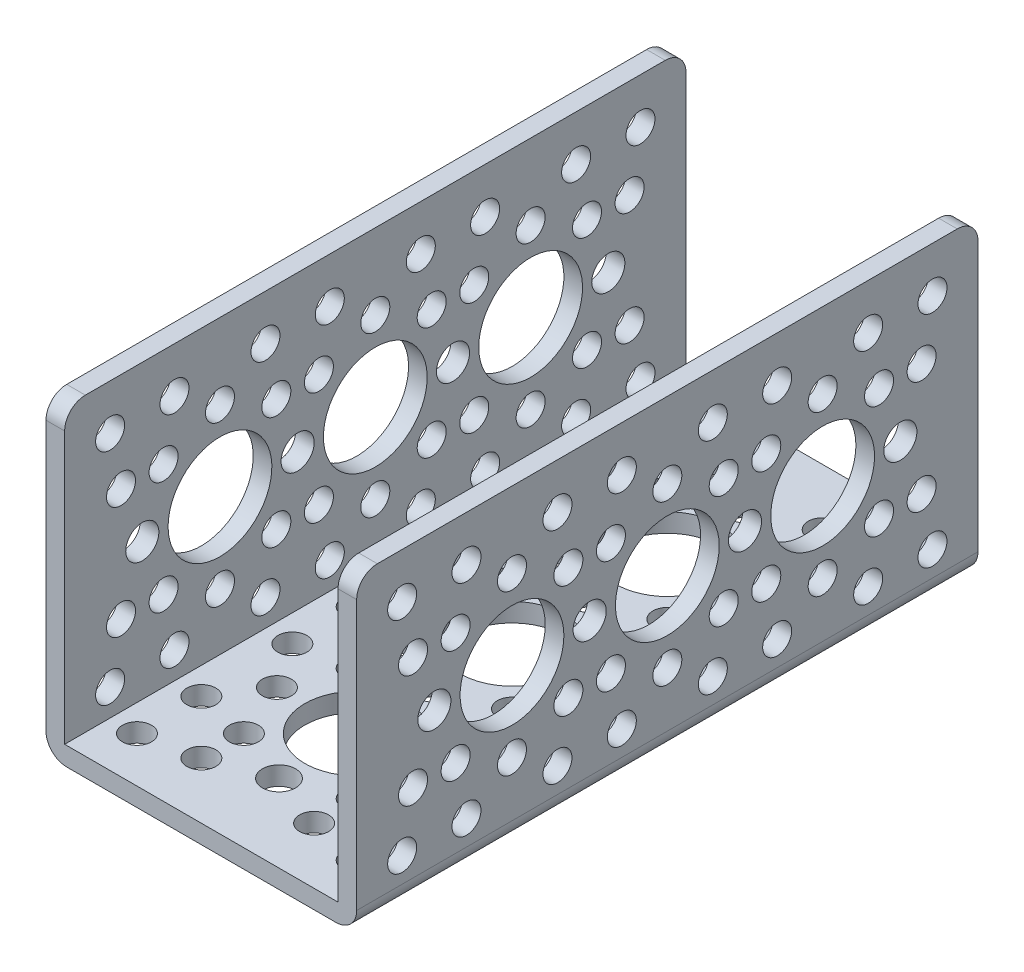
SolidWorks part; units mm, degrees
ref_plane "Front Plane" through (0, 0, 0) normal (0, 0, 1) x (1, 0, 0)
ref_plane "Top Plane" through (0, 0, 0) normal (0, 1, 0) x (1, 0, 0)
ref_plane "Right Plane" through (0, 0, 0) normal (1, 0, 0) x (0, 0, -1)
ref_plane "Plane1" through (0, 0, 0) normal (0, -1, 0) x (1, 0, 0)
sketch "Sketch1" plane through (0, 0, 0) normal (0, -1, 0) x (1, 0, 0)
  line L0 (38.1, 76.2) -> (0, 76.2)
  line L1 (0, 76.2) -> (0, 0)
  line L2 (0, 0) -> (38.1, 0)
  line L3 (38.1, 0) -> (38.1, 76.2)
extrude "Boss-Extrude1" add sketch "Sketch1" against normal blind 38.1
sketch "Sketch2" plane through (0, 0, 76.2) normal (0, 0, 1) x (1, 0, 0)
  line L0 (35.814, 38.1) -> (2.286, 38.1)
  line L1 (2.286, 38.1) -> (2.286, 2.286)
  line L2 (2.286, 2.286) -> (35.814, 2.286)
  line L3 (35.814, 2.286) -> (35.814, 38.1)
extrude "Cut-Extrude1" cut sketch "Sketch2" against normal through all
hole_wizard "Hole1" positions "Sketch4" profile "Sketch3" legacy
sketch "Sketch4" plane through (38.1, 0, 0) normal (1, 0, 0) x (0, 0, -1)
  point P0 (-38.1, 19.05)
  point P1 (-19.05, 19.05)
  point P2 (-57.15, 19.05)
sketch "Sketch3" plane through (38.1, 19.05, 38.1) normal (0, 1, 0) x (0, 0, -1)
  line L0 (0, 0) -> (0, 2.286)
  line L1 (0, 2.286) -> (6.3627, 2.286)
  line L2 (6.3627, 2.286) -> (6.3627, 0)
  line L3 (6.3627, 0) -> (0, 0)
  line L4 (0, 110) -> (0, -10) construction
  dimension "Diameter" = 12.7254
  dimension "Depth" = 2.286
hole_wizard "#5 Clearance Hole1" positions "Sketch6" profile "Sketch5" hole size "#5" standard "ANSI Inch"
sketch "Sketch6" plane through (38.1, 0, 0) normal (1, 0, 0) x (0, 0, -1)
  point P0 (-62.7296, 5.5796)
  point P1 (-69.2852, 12.1352)
  point P2 (-62.7296, 32.5204)
  point P3 (-69.2852, 25.9648)
  point P4 (-13.4704, 5.5796)
  point P5 (-6.9148, 12.1352)
  point P6 (-13.4704, 32.5204)
  point P7 (-6.9148, 25.9648)
  point P8 (-43.6796, 5.5796)
  point P9 (-24.6296, 5.5796)
  point P10 (-43.6796, 32.5204)
  point P11 (-24.6296, 32.5204)
  point P12 (-70.6204, 5.5796)
  point P13 (-70.6204, 32.5204)
  point P14 (-51.5704, 5.5796)
  point P15 (-51.5704, 32.5204)
  point P16 (-50.2352, 12.1352)
  point P17 (-57.15, 9.271)
  point P18 (-64.0648, 12.1352)
  point P19 (-64.0648, 25.9648)
  point P20 (-57.15, 28.829)
  point P21 (-31.1852, 12.1352)
  point P22 (-38.1, 9.271)
  point P23 (-45.0148, 12.1352)
  point P24 (-45.0148, 25.9648)
  point P25 (-38.1, 28.829)
  point P26 (-50.2352, 25.9648)
  point P27 (-31.1852, 25.9648)
  point P28 (-32.5204, 5.5796)
  point P29 (-32.5204, 32.5204)
  point P30 (-5.5796, 5.5796)
  point P31 (-5.5796, 32.5204)
  point P32 (-12.1352, 12.1352)
  point P33 (-19.05, 9.271)
  point P34 (-25.9648, 12.1352)
  point P35 (-25.9648, 25.9648)
  point P36 (-19.05, 28.829)
  point P37 (-12.1352, 25.9648)
sketch "Sketch5" plane through (38.1, 5.5796, 62.7296) normal (0, 1, 0) x (0, 0, -1)
  line L0 (0, 0) -> (0, 2.286)
  line L1 (0, 2.286) -> (1.778, 2.286)
  line L2 (1.778, 2.286) -> (1.778, 0)
  line L5 (1.778, 0) -> (0, 0)
  line L11 (0, -6.35) -> (0, 107.95) construction
  dimension "Thru Hole Dia." = 3.556
  dimension "Thru Hole Depth" = 2.286
hole_wizard "#6 Clearance Hole1" positions "Sketch8" profile "Sketch7" hole size "#6" standard "ANSI Inch"
sketch "Sketch8" plane through (38.1, 0, 0) normal (1, 0, 0) x (0, 0, -1)
  point P0 (-66.675, 19.05)
  point P1 (-47.625, 19.05)
  point P2 (-28.575, 19.05)
  point P3 (-9.525, 19.05)
sketch "Sketch7" plane through (38.1, 19.05, 66.675) normal (0, 1, 0) x (0, 0, -1)
  line L0 (0, 0) -> (0, 2.286)
  line L1 (0, 2.286) -> (2.032, 2.286)
  line L2 (2.032, 2.286) -> (2.032, 0)
  line L5 (2.032, 0) -> (0, 0)
  line L11 (0, -6.35) -> (0, 107.95) construction
  dimension "Thru Hole Dia." = 4.064
  dimension "Thru Hole Depth" = 2.286
hole_wizard "Hole2" positions "Sketch10" profile "Sketch9" legacy
sketch "Sketch10" plane through (0, 0, 0) normal (0, -1, 0) x (-1, 0, 0)
  point P0 (-19.05, -57.15)
  point P1 (-19.05, -38.1)
  point P2 (-19.05, -19.05)
sketch "Sketch9" plane through (19.05, 0, 57.15) normal (1, 0, 0) x (0, 0, -1)
  line L0 (0, 0) -> (0, 38.1)
  line L1 (0, 38.1) -> (6.3627, 38.1)
  line L2 (6.3627, 38.1) -> (6.3627, 0)
  line L3 (6.3627, 0) -> (0, 0)
  line L4 (0, 110) -> (0, -10) construction
  dimension "Diameter" = 12.7254
  dimension "Depth" = 38.1
hole_wizard "#6 Clearance Hole2" positions "Sketch12" profile "Sketch11" hole size "#6" standard "ANSI Inch"
sketch "Sketch12" plane through (0, 0, 0) normal (0, -1, 0) x (-1, 0, 0)
  point P0 (-19.05, -66.675)
  point P1 (-19.05, -47.625)
  point P2 (-19.05, -28.575)
  point P3 (-19.05, -9.525)
sketch "Sketch11" plane through (19.05, 0, 66.675) normal (1, 0, 0) x (0, 0, -1)
  line L0 (0, 0) -> (0, 38.1)
  line L1 (0, 38.1) -> (2.032, 38.1)
  line L2 (2.032, 38.1) -> (2.032, 0)
  line L5 (2.032, 0) -> (0, 0)
  line L11 (0, -6.35) -> (0, 107.95) construction
  dimension "Thru Hole Dia." = 4.064
  dimension "Thru Hole Depth" = 38.1
hole_wizard "#5 Clearance Hole2" positions "Sketch14" profile "Sketch13" hole size "#5" standard "ANSI Inch"
sketch "Sketch14" plane through (0, 0, 0) normal (0, -1, 0) x (-1, 0, 0)
  point P0 (-5.5796, -70.6204)
  point P1 (-5.5796, -62.7296)
  point P2 (-12.1352, -69.2852)
  point P3 (-32.5204, -70.6204)
  point P4 (-32.5204, -62.7296)
  point P5 (-25.9648, -69.2852)
  point P6 (-5.5796, -51.5704)
  point P7 (-5.5796, -43.6796)
  point P8 (-32.5204, -51.5704)
  point P9 (-32.5204, -43.6796)
  point P10 (-12.1352, -50.2352)
  point P11 (-9.271, -57.15)
  point P12 (-12.1352, -64.0648)
  point P13 (-25.9648, -64.0648)
  point P14 (-28.829, -57.15)
  point P15 (-25.9648, -50.2352)
  point P16 (-9.271, -38.1)
  point P17 (-12.1352, -45.0148)
  point P18 (-25.9648, -45.0148)
  point P19 (-28.829, -38.1)
  point P20 (-5.5796, -32.5204)
  point P21 (-5.5796, -24.6296)
  point P22 (-12.1352, -31.1852)
  point P23 (-32.5204, -32.5204)
  point P24 (-32.5204, -24.6296)
  point P25 (-25.9648, -31.1852)
  point P26 (-5.5796, -5.5796)
  point P27 (-5.5796, -13.4704)
  point P28 (-12.1352, -6.9148)
  point P29 (-32.5204, -5.5796)
  point P30 (-32.5204, -13.4704)
  point P31 (-25.9648, -6.9148)
  point P32 (-12.1352, -12.1352)
  point P33 (-9.271, -19.05)
  point P34 (-12.1352, -25.9648)
  point P35 (-25.9648, -25.9648)
  point P36 (-28.829, -19.05)
  point P37 (-25.9648, -12.1352)
sketch "Sketch13" plane through (5.5796, 0, 70.6204) normal (1, 0, 0) x (0, 0, -1)
  line L0 (0, 0) -> (0, 38.1)
  line L1 (0, 38.1) -> (1.778, 38.1)
  line L2 (1.778, 38.1) -> (1.778, 0)
  line L5 (1.778, 0) -> (0, 0)
  line L11 (0, -6.35) -> (0, 107.95) construction
  dimension "Thru Hole Dia." = 3.556
  dimension "Thru Hole Depth" = 38.1
hole_wizard "Hole3" positions "Sketch16" profile "Sketch15" legacy
sketch "Sketch16" plane through (0, 0, 0) normal (-1, 0, 0) x (0, 0, 1)
  point P0 (38.1, 19.05)
  point P1 (19.05, 19.05)
  point P2 (57.15, 19.05)
sketch "Sketch15" plane through (0, 19.05, 38.1) normal (0, 1, 0) x (0, 0, 1)
  line L0 (0, 0) -> (0, 38.1)
  line L1 (0, 38.1) -> (6.3627, 38.1)
  line L2 (6.3627, 38.1) -> (6.3627, 0)
  line L3 (6.3627, 0) -> (0, 0)
  line L4 (0, 110) -> (0, -10) construction
  dimension "Diameter" = 12.7254
  dimension "Depth" = 38.1
hole_wizard "#5 Clearance Hole3" positions "Sketch18" profile "Sketch17" hole size "#5" standard "ANSI Inch"
sketch "Sketch18" plane through (0, 0, 0) normal (-1, 0, 0) x (0, 0, 1)
  point P0 (62.7296, 5.5796)
  point P1 (69.2852, 12.1352)
  point P2 (62.7296, 32.5204)
  point P3 (69.2852, 25.9648)
  point P4 (13.4704, 5.5796)
  point P5 (6.9148, 12.1352)
  point P6 (13.4704, 32.5204)
  point P7 (6.9148, 25.9648)
  point P8 (43.6796, 5.5796)
  point P9 (24.6296, 5.5796)
  point P10 (43.6796, 32.5204)
  point P11 (24.6296, 32.5204)
  point P12 (70.6204, 5.5796)
  point P13 (70.6204, 32.5204)
  point P14 (51.5704, 5.5796)
  point P15 (51.5704, 32.5204)
  point P16 (50.2352, 12.1352)
  point P17 (57.15, 9.271)
  point P18 (64.0648, 12.1352)
  point P19 (64.0648, 25.9648)
  point P20 (57.15, 28.829)
  point P21 (31.1852, 12.1352)
  point P22 (38.1, 9.271)
  point P23 (45.0148, 12.1352)
  point P24 (45.0148, 25.9648)
  point P25 (38.1, 28.829)
  point P26 (50.2352, 25.9648)
  point P27 (31.1852, 25.9648)
  point P28 (32.5204, 5.5796)
  point P29 (32.5204, 32.5204)
  point P30 (5.5796, 5.5796)
  point P31 (5.5796, 32.5204)
  point P32 (12.1352, 12.1352)
  point P33 (19.05, 9.271)
  point P34 (25.9648, 12.1352)
  point P35 (25.9648, 25.9648)
  point P36 (19.05, 28.829)
  point P37 (12.1352, 25.9648)
sketch "Sketch17" plane through (0, 5.5796, 62.7296) normal (0, 1, 0) x (0, 0, 1)
  line L0 (0, 0) -> (0, 38.1)
  line L1 (0, 38.1) -> (1.778, 38.1)
  line L2 (1.778, 38.1) -> (1.778, 0)
  line L5 (1.778, 0) -> (0, 0)
  line L11 (0, -6.35) -> (0, 107.95) construction
  dimension "Thru Hole Dia." = 3.556
  dimension "Thru Hole Depth" = 38.1
hole_wizard "#6 Clearance Hole3" positions "Sketch20" profile "Sketch19" hole size "#6" standard "ANSI Inch"
sketch "Sketch20" plane through (0, 0, 0) normal (-1, 0, 0) x (0, 0, 1)
  point P0 (66.675, 19.05)
  point P1 (47.625, 19.05)
  point P2 (28.575, 19.05)
  point P3 (9.525, 19.05)
sketch "Sketch19" plane through (0, 19.05, 66.675) normal (0, 1, 0) x (0, 0, 1)
  line L0 (0, 0) -> (0, 38.1)
  line L1 (0, 38.1) -> (2.032, 38.1)
  line L2 (2.032, 38.1) -> (2.032, 0)
  line L5 (2.032, 0) -> (0, 0)
  line L11 (0, -6.35) -> (0, 107.95) construction
  dimension "Thru Hole Dia." = 4.064
  dimension "Thru Hole Depth" = 38.1
fillet "Fillet1" radius 2.54 6 edges at (1.143, 38.1, 76.2) (36.957, 38.1, 76.2) (36.957, 38.1, 0) (38.1, 0, 38.1) (1.143, 38.1, 0) (0, 0, 38.1)
